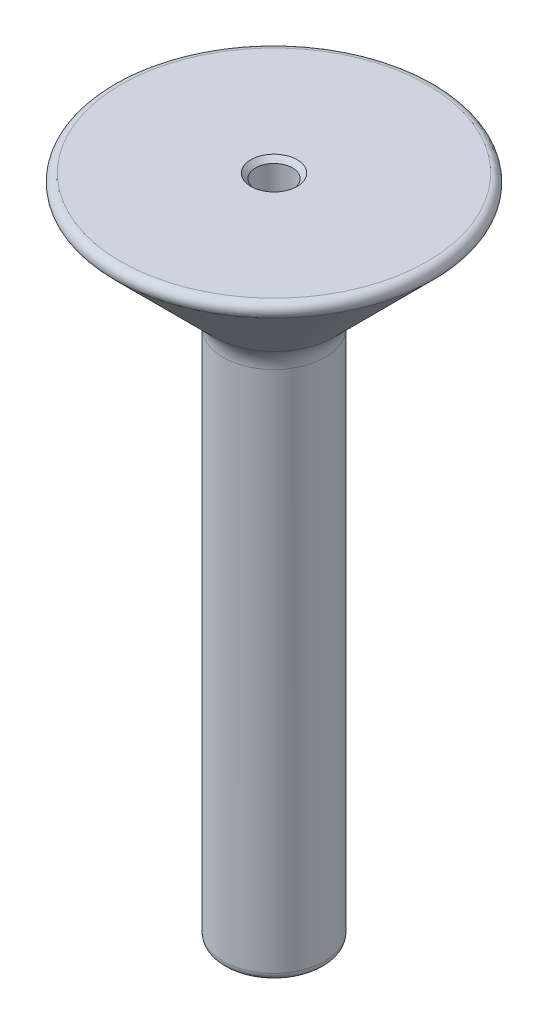
SolidWorks part; units mm, degrees
ref_plane "Front Plane" through (0, 0, 0) normal (0, 0, 1) x (1, 0, 0)
ref_plane "Top Plane" through (0, 0, 0) normal (0, 1, 0) x (1, 0, 0)
ref_plane "Right Plane" through (0, 0, 0) normal (1, 0, 0) x (0, 0, -1)
sketch "Sketch1" plane through (0, 0, 0) normal (0, 0, 1) x (1, 0, 0)
  line L0 (-27.94, 107.95) -> (-8.255, 88.265)
  line L1 (-8.255, 88.265) -> (-8.255, 0)
  line L2 (-8.255, 0) -> (-5.08, 0)
  line L3 (-5.08, 0) -> (-5.08, 12.7)
  line L4 (-5.08, 12.7) -> (0, 12.7)
  line L5 (0, 12.7) -> (0, 98.95)
  line L6 (0, 98.95) -> (-3, 98.95)
  line L7 (-3, 98.95) -> (-3, 107.95)
  line L8 (-3, 107.95) -> (-27.94, 107.95)
  line L9 (-12.7, 92.71) -> (0, 92.71) construction
  line L10 (-19.05, 99.06) -> (0, 99.06) construction
  dimension "D1" = 3
  dimension "D2" = 9
  dimension "D3" = 27.94
  dimension "D4" = 5.08
  dimension "D5" = 12.7
  dimension "D6" = 45
  dimension "D7" = 8.255
  dimension "D8" = 107.95
  dimension "D9" = 6.35
  dimension "D10" = 12.7
revolve "Revolve1" add sketch "Sketch1" angle 360 about L5
chamfer "Chamfer1" distance 0.762 angle 45 2 edges at (0, 0, -5.08) (0, 107.95, -3)
fillet "Fillet1" radius 1.27 1 edges at (0, 0, -8.255)
fillet "Fillet2" radius 1.27 1 edges at (0, 107.95, -27.94)
fillet "Fillet3" radius 5.08 1 edges at (0, 88.265, -8.255)
